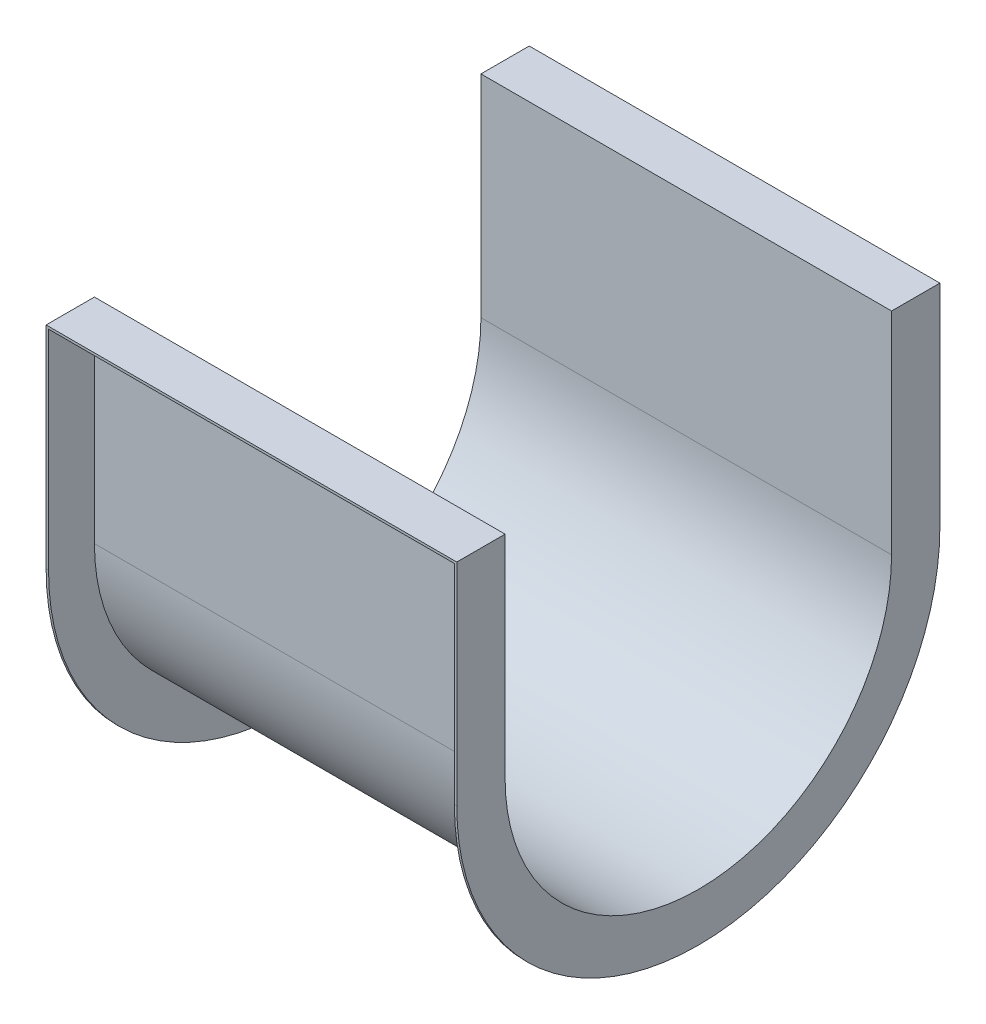
SolidWorks part; units mm, degrees
ref_plane "Front" through (0, 0, 0) normal (0, 0, 1) x (1, 0, 0)
ref_plane "Top" through (0, 0, 0) normal (0, 1, 0) x (1, 0, 0)
ref_plane "Right" through (0, 0, 0) normal (1, 0, 0) x (0, 0, -1)
sketch "Croquis1" plane through (0, 0, 0) normal (1, 0, 0) x (0, 0, -1)
  line L0 (80, 0) -> (100, 0)
  line L1 (100, 0) -> (100, -83.7)
  line L2 (33.9999, -183.7) -> (0, -183.7) construction
  line L3 (0, 0) -> (0, -183.7) construction
  line L8 (-33.9999, -183.7) -> (0, -183.7) construction
  line L9 (-100, 0) -> (-100, -83.7)
  line L10 (-80, 0) -> (-100, 0)
  line L12 (-80, 0) -> (-80, -83.7)
  line L13 (80, 0) -> (80, -83.7)
  line L15 (-80, -20) -> (-80, -83.7) construction
  line L16 (80, -20) -> (80, -83.7) construction
  line L17 (0, 0) -> (-100, 0) construction
  line L18 (0, -20) -> (-80, -20) construction
  line L19 (0, 0) -> (100, 0) construction
  line L20 (0, -20) -> (80, -20) construction
  arc A0 (0, -183.7) -> (100, -83.7) centre (0, -83.7) ccw
  arc A1 (0, -183.7) -> (-100, -83.7) centre (0, -83.7) cw
  arc A2 (0, -163.7) -> (-80, -83.7) centre (0, -83.7) cw
  arc A3 (0, -163.7) -> (80, -83.7) centre (0, -83.7) ccw
  dimension "D3" = 200
  dimension "D4" = 20
  dimension "D1" = 100
  dimension "D2" = 183.7
extrude "Saliente-Extruir1" add sketch "Croquis1" along normal blind 170
sketch "Croquis2" plane through (0, 0, 0) normal (0, 1, 0) x (1, 0, 0)
  line L1 (0, 100) -> (170, 100)
  line L2 (0, 100) -> (0, 80)
  line L3 (0, 80) -> (170, 80)
  line L4 (170, 100) -> (170, 80)
  line L5 (0, 100) -> (170, 80) construction
  line L6 (0, 80) -> (170, 100) construction
  line L7 (170, -80) -> (0, -80)
  line L8 (170, -80) -> (170, -100)
  line L9 (170, -100) -> (0, -100)
  line L10 (0, -80) -> (0, -100)
  line L11 (170, -80) -> (0, -100) construction
  line L12 (170, -100) -> (0, -80) construction
  point P4 (85, 90)
  point P11 (85, -90)
extrude "Saliente-Extruir2" add sketch "Croquis2" along normal blind 3.7
shell "Vaciado1" thickness 1
